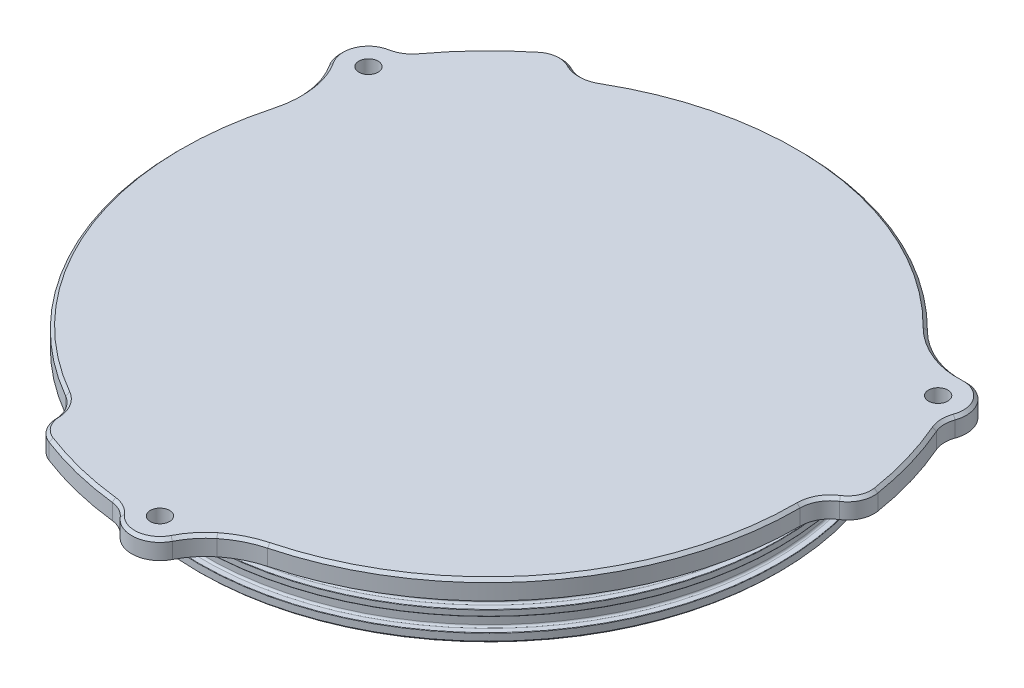
SolidWorks part; units mm, degrees
material "6061-T6 (SS)"
ref_plane "Front Plane" through (0, 0, 0) normal (0, 0, 1) x (1, 0, 0)
ref_plane "Top Plane" through (0, 0, 0) normal (0, 1, 0) x (1, 0, 0)
ref_plane "Right Plane" through (0, 0, 0) normal (1, 0, 0) x (0, 0, -1)
sketch "Sketch1" plane through (0, 0, 0) normal (0, 0, 1) x (1, 0, 0)
  line L0 (0, 0) -> (0, 50000) construction
  line L1 (0, 0) -> (-104.775, 0)
  line L2 (-104.775, 0) -> (-104.775, -6.35)
  line L3 (-104.775, -6.35) -> (-98.7298, -6.35)
  line L4 (-98.0948, -6.985) -> (-98.0948, -8.763)
  line L5 (-97.9678, -8.89) -> (-96.2152, -8.89)
  line L6 (-95.5802, -9.525) -> (-95.5802, -13.0048)
  line L7 (-96.2152, -13.6398) -> (-97.9678, -13.6398)
  line L8 (-98.0948, -13.7668) -> (-98.0948, -15.5448)
  line L9 (-97.9678, -15.6718) -> (-96.2152, -15.6718)
  line L10 (-95.5802, -16.3068) -> (-95.5802, -19.7866)
  line L11 (-96.2152, -20.4216) -> (-97.9678, -20.4216)
  line L12 (-98.0948, -20.5486) -> (-98.0948, -23.495)
  line L13 (-98.0948, -23.495) -> (-90.17, -23.495)
  line L14 (-90.17, -23.495) -> (-90.17, -6.35)
  line L15 (-90.17, -6.35) -> (0, -6.35)
  line L16 (0, -6.35) -> (0, 0)
  arc A0 (-95.5802, -19.7866) -> (-96.2152, -20.4216) centre (-96.2152, -19.7866) cw
  arc A1 (-96.2152, -15.6718) -> (-95.5802, -16.3068) centre (-96.2152, -16.3068) cw
  arc A2 (-95.5802, -13.0048) -> (-96.2152, -13.6398) centre (-96.2152, -13.0048) cw
  arc A3 (-96.2152, -8.89) -> (-95.5802, -9.525) centre (-96.2152, -9.525) cw
  arc A5 (-98.7298, -6.35) -> (-98.0948, -6.985) centre (-98.7298, -6.985) cw
  arc A6 (-97.9678, -20.4216) -> (-98.0948, -20.5486) centre (-97.9678, -20.5486) ccw
  arc A7 (-98.0948, -15.5448) -> (-97.9678, -15.6718) centre (-97.9678, -15.5448) ccw
  arc A8 (-97.9678, -13.6398) -> (-98.0948, -13.7668) centre (-97.9678, -13.7668) ccw
  arc A9 (-98.0948, -8.763) -> (-97.9678, -8.89) centre (-97.9678, -8.763) ccw
  point P25 (-95.5802, -13.6398)
  point P28 (-95.5802, -8.89)
  point P33 (-98.0948, -6.35)
  point P42 (-98.0948, -8.89)
  dimension "D9" = 0.635
  dimension "D10" = 0.127
  dimension "D11" = 0.635
  dimension "D1" = 209.55
  dimension "D2" = 196.1896
  dimension "D3" = 191.1604
  dimension "D4" = 180.34
  dimension "D5" = 6.35
  dimension "D6" = 23.495
  dimension "D7" = 2.54
  dimension "D8" = 4.7498
revolve "Revolve1" add sketch "Sketch1" angle 360 about L0
chamfer "Chamfer1" distance 0.635 angle 45 1 edges at (0, -23.495, -98.0948)
sketch "Sketch3" plane through (0, 0, 0) normal (0, 1, 0) x (1, 0, 0)
  line L0 (0, 0) -> (0, 50000) construction
  line L1 (0, 0) -> (43301.2702, 25000) construction
  arc A0 (105.2021, 52.3448) -> (95.702, 65.0725) centre (96.2371, 55.5625) ccw
  circle A1 centre (0, 0) radius 104.775 construction
  arc A2 (104.7744, 0.35) -> (74.4487, 73.7238) centre (0, 0) ccw
  arc A3 (109.5057, 8.972) -> (113.5375, 17.8687) centre (104.7556, 16.4866) ccw
  arc A4 (74.4487, 73.7238) -> (85.1178, 66.7404) centre (96.1064, 95.1707) ccw
  arc A5 (105.2021, 52.3448) -> (105.4158, 45.7992) centre (113.5695, 49.3416) ccw
  arc A6 (85.1178, 66.7404) -> (95.702, 65.0725) centre (94.275, 90.4323) ccw
  arc A7 (113.5375, 17.8687) -> (105.4158, 45.7992) centre (0, 0) ccw
  circle A8 centre (0, 0) radius 104.775 construction
  arc A9 (109.5057, 8.972) -> (104.7744, 0.35) centre (114.9344, 0.3839) ccw
  dimension "D2" = 8.89
  dimension "D3" = 9.525
  dimension "D4" = 38.1
  dimension "D7" = 10.16
  dimension "D6" = 30.48
  dimension "D8" = 25.4
  dimension "D1" = 60
  dimension "D5" = 111.125
  dimension "D9" = 15.24
extrude "Boss-Extrude2" add sketch "Sketch3" against normal up to surface (6.35 mm away) up to face at (0, -6.35, -98.7298)
hole_wizard "1/4 Clearance Hole1" positions "Sketch5" profile "Sketch6" hole size "1/4" standard "Ansi Inch" end condition through all
sketch "Sketch5" plane through (0, 0, 0) normal (0, 1, 0) x (-1, 0, 0)
  arc A0 (-105.2021, -52.3448) -> (-95.702, -65.0725) centre (-96.2371, -55.5625) ccw construction
  point P0 (-96.2371, -55.5625)
sketch "Sketch6" plane through (96.2371, 0, -55.5625) normal (1, 0, 0) x (0, 0, 1)
  line L0 (0, 0) -> (0, 23.495)
  line L1 (0, 23.495) -> (3.2639, 23.495)
  line L2 (3.2639, 23.495) -> (3.2639, 0)
  line L5 (3.2639, 0) -> (0, 0)
  line L11 (0, -6.35) -> (0, 107.95) construction
  dimension "Thru Hole Dia." = 6.5278
  dimension "Thru Hole Depth" = 23.495
pattern_circular "CirPattern2" count 3 over 360 about axis through (0, 0, 0) along (0, 1, 0) of "1/4 Clearance Hole1", "Boss-Extrude2"
chamfer "Chamfer2" distance 1.016 angle 45 24 edges at (-9.8622, 0, 115.185) (-27.3895, 0, 111.6238) (1.1176, 0, 120.5842) (-45.3266, 0, 104.142) (11.4274, 0, 110.8912) (-48.4483, 0, 94.4581) (20.6272, 0, 103.6085) (-96.8306, 0, 40.0206) (83.0741, 0, 63.8474) (-100.0412, 0, -33.9405) (106.0273, 0, -5.2716) (-101.7483, 0, -45.5492) (112.8529, 0, -12.817) (-104.9878, 0, -59.3242) (110.3638, 0, -32.0919) (-94.8221, 0, -66.1334) (104.6842, 0, -49.0516) (-82.9743, 0, -79.5319) (103.8702, 0, -61.26) (-67.5263, 0, -91.325) (90.3209, 0, -65.342) (-57.579, 0, -89.1865) (79.414, 0, -69.6679) (13.7565, 0, -103.868)
